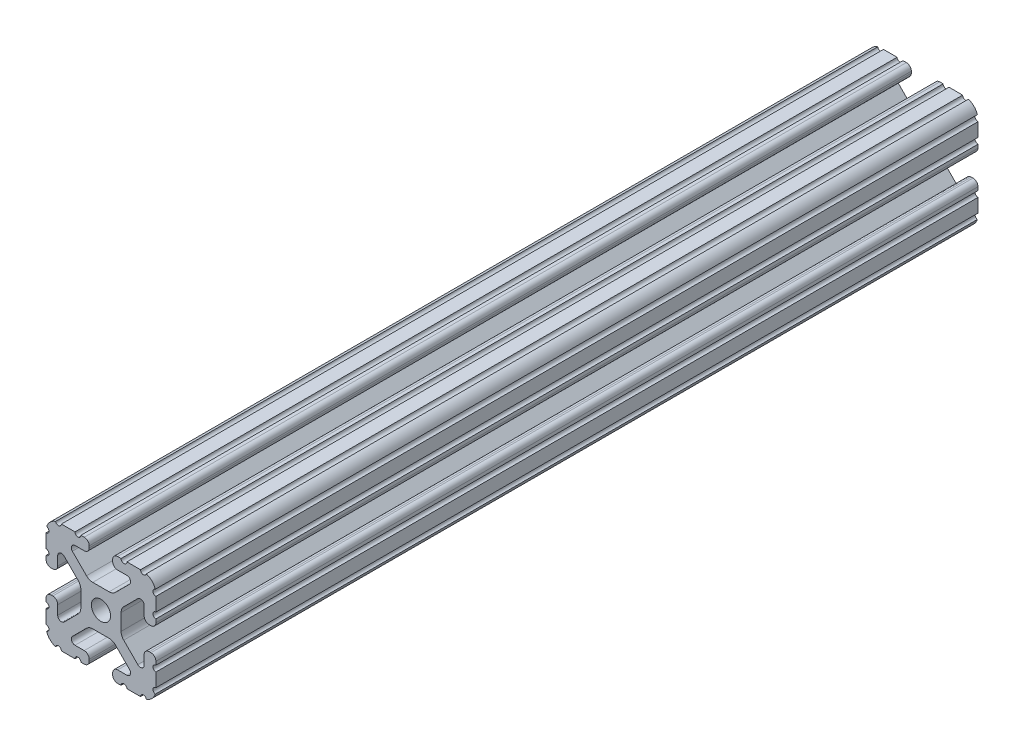
SolidWorks part; units mm, degrees
ref_plane "Front Plane" through (0, 0, 0) normal (0, 0, 1) x (1, 0, 0)
ref_plane "Top Plane" through (0, 0, 0) normal (0, 1, 0) x (1, 0, 0)
ref_plane "Right Plane" through (0, 0, 0) normal (1, 0, 0) x (0, 0, -1)
sketch "Sketch2" plane through (0, 0, 0) normal (0, 0, 1) x (1, 0, 0)
  line L0 (0, 19.05) -> (0, -19.05) construction
  line L1 (-19.05, 0) -> (19.05, 0) construction
  line L2 (4.064, -19.05) -> (19.05, -19.05)
  line L3 (19.05, -19.05) -> (19.05, -4.064)
  line L4 (4.064, -19.05) -> (4.064, -14.986)
  line L5 (4.064, -14.986) -> (12.1123, -14.986)
  line L6 (12.1123, -14.986) -> (4.1113, -6.985)
  line L7 (0, 0) -> (19.05, -19.05) construction
  line L8 (19.05, -4.064) -> (14.986, -4.064)
  line L9 (14.986, -4.064) -> (14.986, -12.1123)
  line L10 (14.986, -12.1123) -> (6.985, -4.1113)
  circle A0 centre (0, 0) radius 3.3274
  arc A1 (8.9963, -14.986) -> (9.909, -12.7826) centre (8.9963, -13.6953) ccw construction
  point P8 (0, -6.985)
  dimension "Center Hole Diameter" = 6.6548
  dimension "Rail Height" = 38.1
  dimension "Rail Width" = 38.1
  dimension "T-Slot Width" = 8.128
  dimension "Slot Inner Width" = 20.574
  dimension "Thickness" = 4.064
  dimension "Slot Depth" = 8.001
  dimension "D1" = 4.064
sketch "Sketch3" plane through (0, 0, 0) normal (1, 0, 0) x (0, 0, -1)
  line L0 (-142.515, -19.05) -> (142.515, -19.05) construction
  line L1 (-117.115, 0) -> (117.115, 0) construction
  dimension "Length" = 285.03
  dimension "D1" = 25.4
sketch "Sketch4" plane through (0, 0, 0) normal (0, 0, 1) x (1, 0, 0)
  line L0 (5.7912, -19.05) -> (14.3002, -19.05)
  line L1 (4.064, -19.05) -> (19.05, -19.05) construction
  line L2 (4.064, -19.05) -> (4.064, -14.986) construction
  line L3 (4.064, -14.986) -> (12.1123, -14.986) construction
  line L4 (4.064, -16.7132) -> (4.064, -17.3228)
  line L5 (5.7912, -14.986) -> (8.9963, -14.986)
  line L6 (0, -6.985) -> (2.833, -6.985)
  line L7 (12.1123, -14.986) -> (4.1113, -6.985) construction
  line L8 (5.0152, -7.8889) -> (9.909, -12.7826)
  line L9 (19.05, -19.05) -> (19.05, -4.064) construction
  line L10 (14.986, -12.1123) -> (6.985, -4.1113) construction
  line L11 (14.986, -4.064) -> (14.986, -12.1123) construction
  line L12 (14.986, -8.9963) -> (14.986, -5.7912)
  line L13 (19.05, -4.064) -> (14.986, -4.064) construction
  line L14 (16.7132, -4.064) -> (17.3228, -4.064)
  line L15 (19.05, -5.7912) -> (19.05, -14.3002)
  line L16 (12.7826, -9.909) -> (7.8889, -5.0152)
  line L17 (6.985, 0) -> (6.985, -2.833)
  line L18 (-19.05, 0) -> (19.05, 0) construction
  line L19 (0, -6.985) -> (0, -3.3274)
  line L20 (0, 19.05) -> (0, -19.05) construction
  line L21 (6.985, 0) -> (3.3274, 0)
  arc A0 (4.064, -17.3228) -> (5.7912, -19.05) centre (5.7912, -17.3228) ccw
  arc A2 (4.064, -16.7132) -> (5.7912, -14.986) centre (5.7912, -16.7132) cw
  arc A3 (8.9963, -14.986) -> (9.909, -12.7826) centre (8.9963, -13.6953) ccw
  arc A4 (2.833, -6.985) -> (5.0152, -7.8889) centre (2.833, -10.0711) cw
  arc A5 (14.3002, -19.05) -> (19.05, -14.3002) centre (14.3002, -14.3002) ccw
  arc A6 (12.7826, -9.909) -> (14.986, -8.9963) centre (13.6953, -8.9963) ccw
  arc A7 (14.986, -5.7912) -> (16.7132, -4.064) centre (16.7132, -5.7912) cw
  arc A8 (17.3228, -4.064) -> (19.05, -5.7912) centre (17.3228, -5.7912) cw
  arc A9 (7.8889, -5.0152) -> (6.985, -2.833) centre (10.0711, -2.833) cw
  circle A10 centre (0, 0) radius 3.3274 construction
  arc A11 (0, -3.3274) -> (3.3274, 0) centre (0, 0) ccw
  dimension "D1" = 4.7498
  dimension "D2" = 3.0861
  dimension "D3" = 1.7272
extrude "Boss-Extrude1" add sketch "Sketch4" along normal mid plane 285.03
sketch "Sketch5" plane through (0, 0, 0) normal (0, 0, 1) x (1, 0, 0)
  line L0 (4.064, -19.05) -> (19.05, -19.05) construction
  line L1 (5.7912, -14.986) -> (8.9963, -14.986) construction
  line L3 (0, 0) -> (19.05, -19.05) construction
  line L4 (8.9963, -14.986) -> (8.9963, -19.05) construction
  line L5 (12.1123, -14.986) -> (4.1113, -6.985) construction
  circle A0 centre (14.7395, -19.05) radius 1.016
  circle A1 centre (7.9803, -19.05) radius 1.016
  circle A2 centre (19.05, -14.7395) radius 1.016
  circle A3 centre (19.05, -7.9803) radius 1.016
  point P10 (7.3938, -14.986)
  point P12 (13.6953, -8.9963)
  dimension "D1" = 2.032
extrude "Cut-Extrude1" cut sketch "Sketch5" against normal through all both and the other way through all
mirror "Mirror1" about plane through (0, 0, 0) normal (1, 0, 0) of bodies 137 134
mirror "Mirror2" about plane through (0, 0, 0) normal (0, 1, 0) of bodies 135
equation "\"D1@Boss-Extrude1\"=\"Length@Sketch3\""
equation "\"D1@Sketch2\"=\"Thickness@Sketch2\""
equation "\"D2@Sketch4\"=\"Slot Inner Width@Sketch2\"*0.15"
equation "\"D1@Sketch4\"=\"D3@Sketch4\"*2.75"
equation "\"D3@Sketch4\"=\"Thickness@Sketch2\"*0.425"
equation "\"D1@Sketch5\"=\"Thickness@Sketch2\"*0.5"
